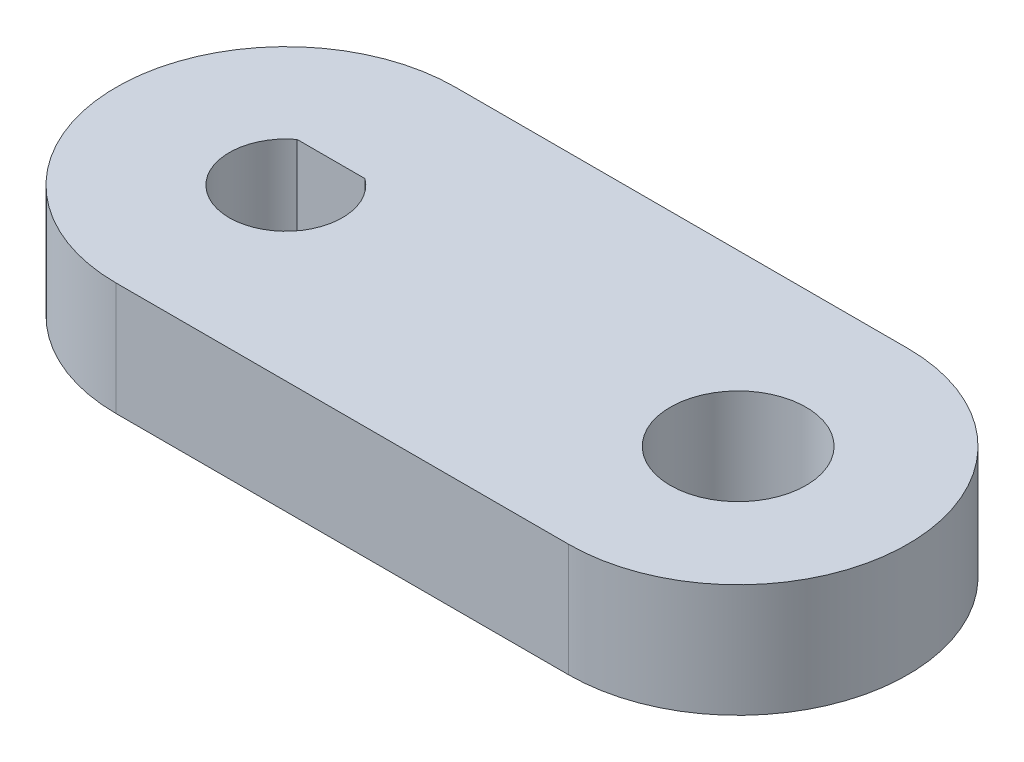
SolidWorks part; units mm, degrees
ref_plane "Front Plane" through (0, 0, 0) normal (0, 0, 1) x (1, 0, 0)
ref_plane "Top Plane" through (0, 0, 0) normal (0, 1, 0) x (1, 0, 0)
ref_plane "Right Plane" through (0, 0, 0) normal (1, 0, 0) x (0, 0, -1)
sketch "Sketch1" plane through (0, 0, 0) normal (0, 1, 0) x (1, 0, 0)
  line L0 (0, 0) -> (20, 0) construction
  line L1 (-55, 0) -> (55, 0) construction
  line L2 (0, 7.5) -> (20, 7.5)
  line L3 (0, -7.5) -> (20, -7.5)
  line L4 (1.5, 2) -> (-1.5, 2)
  arc A0 (0, 7.5) -> (0, -7.5) centre (0, 0) ccw
  arc A1 (20, -7.5) -> (20, 7.5) centre (20, 0) ccw
  circle A2 centre (20, 0) radius 3
  arc A3 (-1.5, 2) -> (1.5, 2) centre (0, 0) ccw
  point P5 (10, 0)
  dimension "D1" = 5
  dimension "D2" = 6
  dimension "D4" = 2
  dimension "D3" = 15
  dimension "D5" = 20
extrude "Boss-Extrude1" add sketch "Sketch1" along normal blind 5
